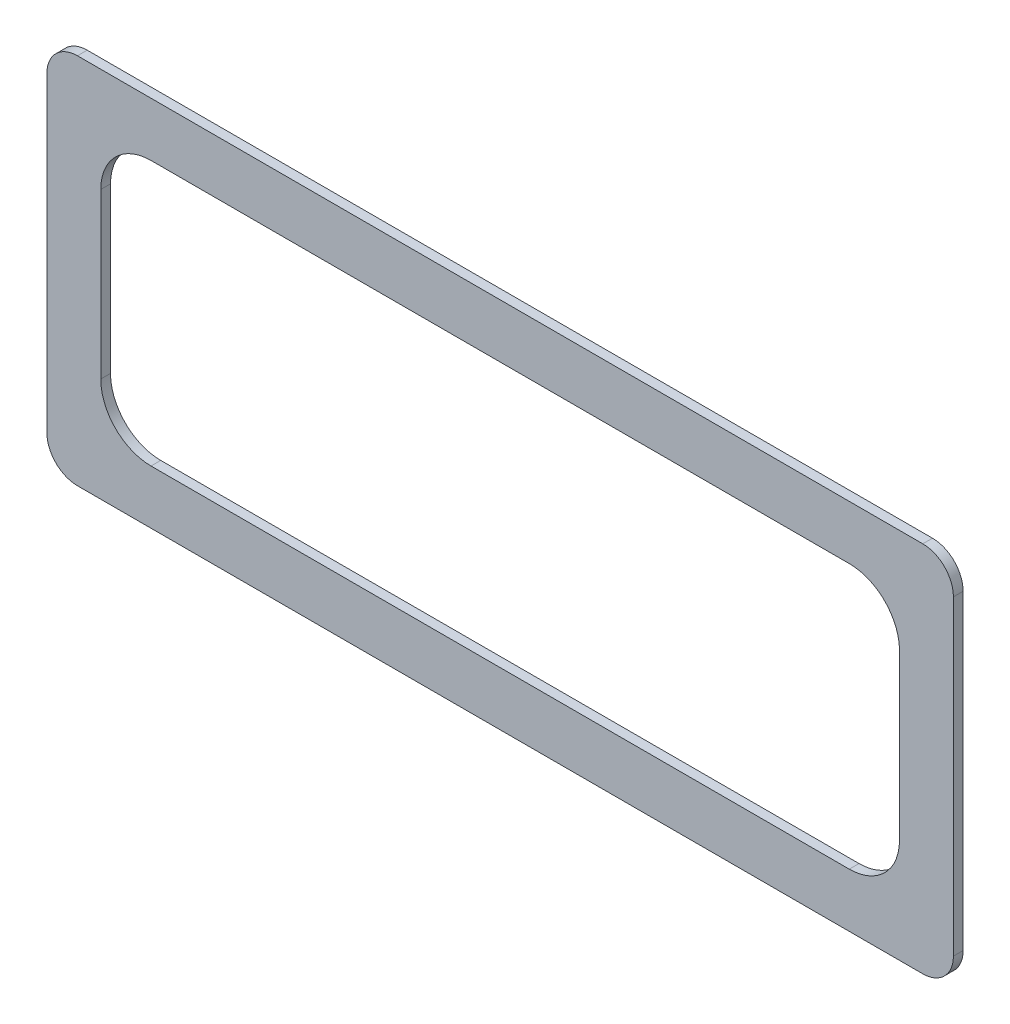
SolidWorks part; units mm, degrees
material "Silicon Rubber"
ref_plane "Front Plane" through (0, 0, 0) normal (0, 0, 1) x (1, 0, 0)
ref_plane "Top Plane" through (0, 0, 0) normal (0, 1, 0) x (1, 0, 0)
ref_plane "Right Plane" through (0, 0, 0) normal (1, 0, 0) x (0, 0, -1)
sketch "Sketch1" plane through (0, 0, 0) normal (0, 0, 1) x (1, 0, 0)
  line L27 (34, -12.7) -> (34, 12.7)
  line L28 (-37.5, -15.2) -> (31.5, -15.2)
  line L29 (-40, 12.7) -> (-40, -12.7)
  line L30 (31.5, 15.2) -> (-37.5, 15.2)
  line L40 (29.6, -6.7) -> (29.6, 6.7)
  line L41 (-31.5, -10.8) -> (25.5, -10.8)
  line L42 (-35.6, 6.7) -> (-35.6, -6.7)
  line L43 (25.5, 10.8) -> (-31.5, 10.8)
  arc A25 (34, 12.7) -> (31.5, 15.2) centre (31.5, 12.7) ccw
  arc A26 (31.5, -15.2) -> (34, -12.7) centre (31.5, -12.7) ccw
  arc A27 (-40, -12.7) -> (-37.5, -15.2) centre (-37.5, -12.7) ccw
  arc A28 (-37.5, 15.2) -> (-40, 12.7) centre (-37.5, 12.7) ccw
  arc A35 (29.6, 6.7) -> (25.5, 10.8) centre (25.5, 6.7) ccw
  arc A36 (25.5, -10.8) -> (29.6, -6.7) centre (25.5, -6.7) ccw
  arc A37 (-35.6, -6.7) -> (-31.5, -10.8) centre (-31.5, -6.7) ccw
  arc A38 (-31.5, 10.8) -> (-35.6, 6.7) centre (-31.5, 6.7) ccw
extrude "Boss-Extrude1" add sketch "Sketch1" along normal blind 0.7937
